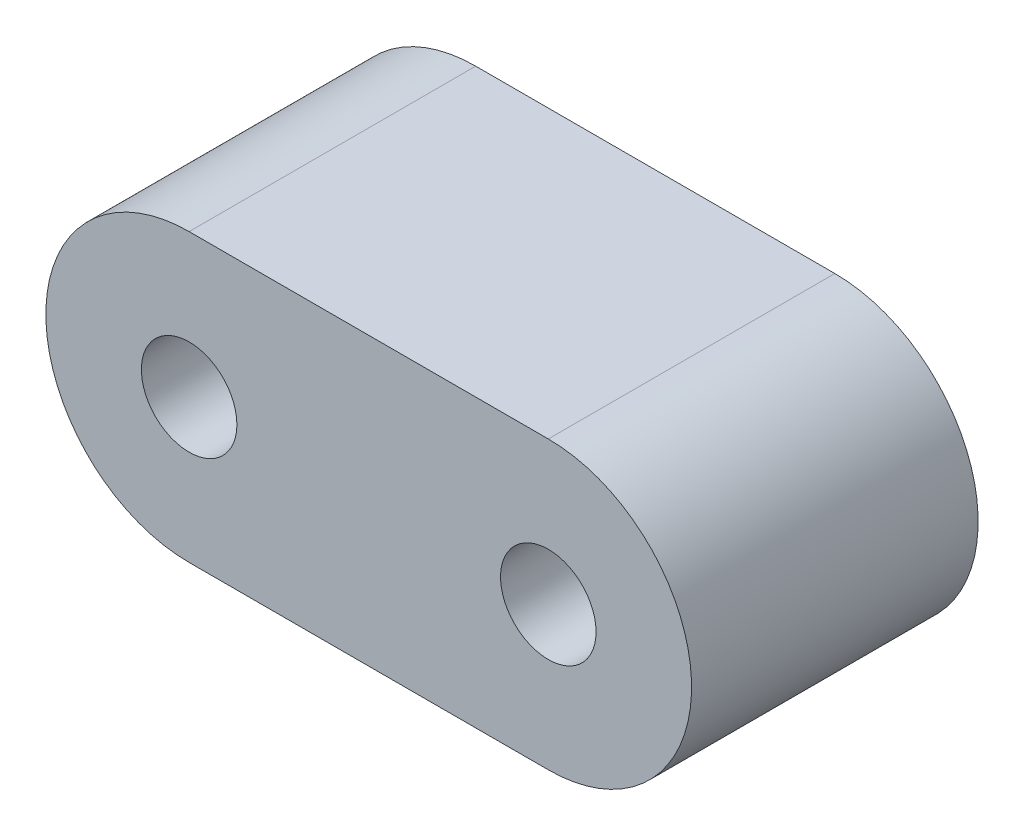
SolidWorks part; units mm, degrees
ref_plane "Front Plane" through (0, 0, 0) normal (0, 0, 1) x (1, 0, 0)
ref_plane "Top Plane" through (0, 0, 0) normal (0, 1, 0) x (1, 0, 0)
ref_plane "Right Plane" through (0, 0, 0) normal (1, 0, 0) x (0, 0, -1)
sketch "Sketch1" plane through (0, 0, 0) normal (0, 0, 1) x (1, 0, 0)
  line L0 (0, 0) -> (3.76, 0) construction
  line L1 (0, 1.5) -> (3.76, 1.5)
  line L2 (0, -1.5) -> (3.76, -1.5)
  arc A0 (0, 1.5) -> (0, -1.5) centre (0, 0) ccw
  arc A1 (3.76, -1.5) -> (3.76, 1.5) centre (3.76, 0) ccw
  circle A2 centre (0, 0) radius 0.5
  circle A3 centre (3.76, 0) radius 0.5
  point P3 (1.88, 0)
  dimension "D1" = 3.76
  dimension "D3" = 1
  dimension "D4" = 1
  dimension "D2" = 3
extrude "Boss-Extrude1" add sketch "Sketch1" along normal mid plane 3
